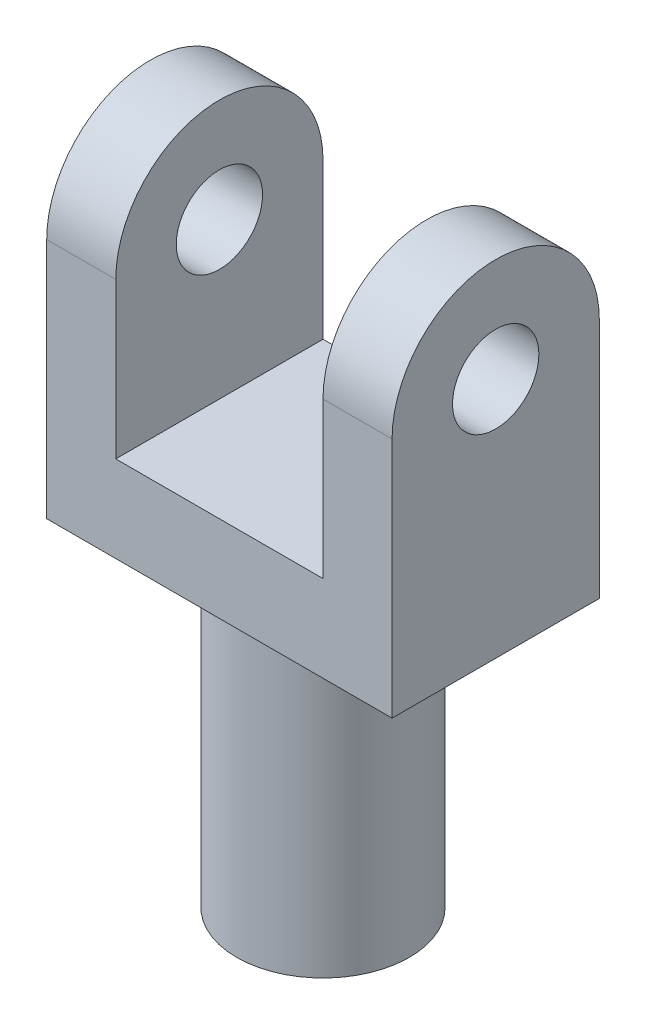
SolidWorks part; units mm, degrees
ref_plane "前视基准面" through (0, 0, 0) normal (0, 0, 1) x (1, 0, 0)
ref_plane "上视基准面" through (0, 0, 0) normal (0, 1, 0) x (1, 0, 0)
ref_plane "右视基准面" through (0, 0, 0) normal (1, 0, 0) x (0, 0, -1)
sketch "草图1" plane through (0, 0, 0) normal (0, 1, 0) x (1, 0, 0)
  circle A0 centre (0, 0) radius 10
extrude "凸台-拉伸1" add sketch "草图1" along normal blind 35
ref_plane "基准面1" through (0, 35, 0) normal (0, 1, 0) x (1, 0, 0)
sketch "草图2" plane through (0, 35, 0) normal (0, 1, 0) x (1, 0, 0)
  line L0 (-20, 12) -> (20, 12)
  line L1 (20, 12) -> (20, -12)
  line L2 (20, -12) -> (-20, -12)
  line L3 (-20, -12) -> (-20, 12)
extrude "凸台-拉伸2" add sketch "草图2" along normal blind 10
ref_plane "基准面2" through (12, 0, 0) normal (1, 0, 0) x (0, 0, -1)
sketch "草图3" plane through (12, 0, 0) normal (1, 0, 0) x (0, 0, -1)
  line L0 (12, 45) -> (12, 63)
  line L1 (-12, 63) -> (-12, 45)
  line L2 (-12, 45) -> (12, 45)
  arc A0 (12, 63) -> (-12, 63) centre (0, 63) ccw
extrude "凸台-拉伸3" add sketch "草图3" along normal blind 8
ref_plane "基准面3" through (-20, 0, 0) normal (1, 0, 0) x (0, 0, -1)
sketch "草图4" plane through (-20, 0, 0) normal (1, 0, 0) x (0, 0, -1)
  line L0 (12, 45) -> (12, 63)
  line L1 (-12, 63) -> (-12, 45)
  line L2 (-12, 45) -> (12, 45)
  arc A0 (12, 63) -> (-12, 63) centre (0, 63) ccw
extrude "凸台-拉伸4" add sketch "草图4" along normal blind 8
sketch "草图5" plane through (-20, 0, 0) normal (1, 0, 0) x (0, 0, -1)
  circle A0 centre (0, 63) radius 5
extrude "切除-拉伸1" cut sketch "草图5" against normal mid plane 152
sketch "草图6" plane through (0, 0, 0) normal (0, 1, 0) x (1, 0, 0)
  circle A0 centre (0, 0) radius 3.4
extrude "切除-拉伸2" cut sketch "草图6" along normal blind 20
